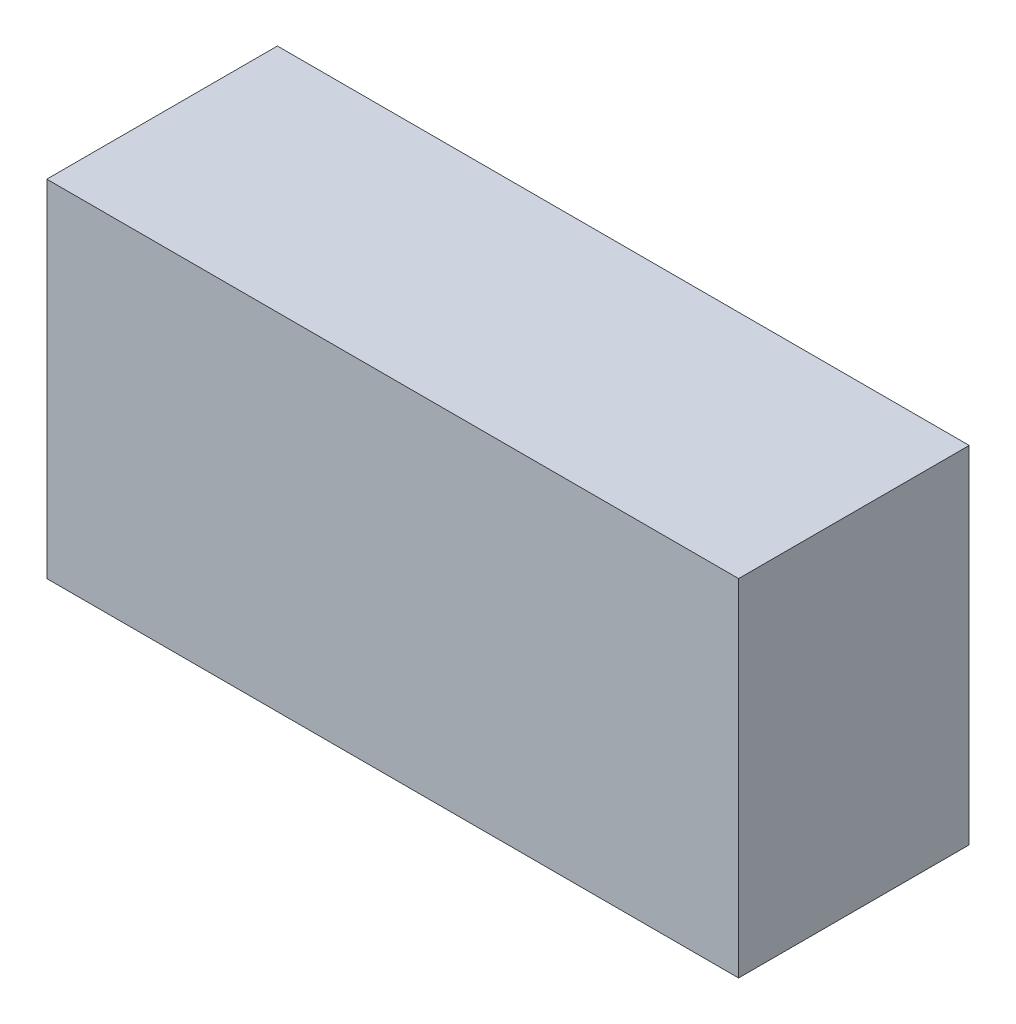
SolidWorks part; units mm, degrees
material "Cedar"
ref_plane "Front" through (0, 0, 0) normal (0, 0, 1) x (1, 0, 0)
ref_plane "Top" through (0, 0, 0) normal (0, 1, 0) x (1, 0, 0)
ref_plane "Right" through (0, 0, 0) normal (1, 0, 0) x (0, 0, -1)
sketch "Sketch1" plane through (0, 0, 0) normal (0, 0, 1) x (1, 0, 0)
  line L1 (-30, 30) -> (30, 30)
  line L2 (-30, 30) -> (-30, 0)
  line L3 (-30, 0) -> (30, 0)
  line L4 (30, 30) -> (30, 0)
  line L5 (-30, 30) -> (30, 0) construction
  line L6 (-30, 0) -> (30, 30) construction
  point P4 (0, 15)
extrude "Boss-Extrude1" add sketch "Sketch1" along normal blind 20
